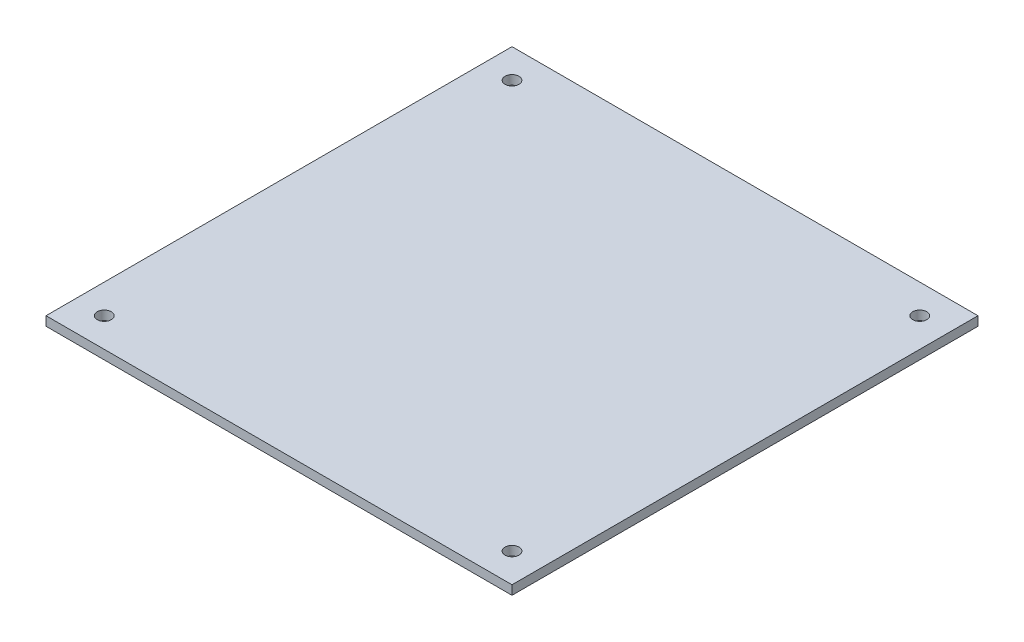
SolidWorks part; units mm, degrees
material "Beryllium S-65C, Vacuum Hot Pressed"
ref_plane "Front Plane" through (0, 0, 0) normal (0, 0, 1) x (1, 0, 0)
ref_plane "Top Plane" through (0, 0, 0) normal (0, 1, 0) x (1, 0, 0)
ref_plane "Right Plane" through (0, 0, 0) normal (1, 0, 0) x (0, 0, -1)
sketch "Sketch1" plane through (0, 0, 0) normal (0, 1, 0) x (1, 0, 0)
  line L1 (50.8, -50.8) -> (-50.8, -50.8)
  line L2 (50.8, -50.8) -> (50.8, 50.8)
  line L3 (50.8, 50.8) -> (-50.8, 50.8)
  line L4 (-50.8, -50.8) -> (-50.8, 50.8)
  line L5 (50.8, -50.8) -> (-50.8, 50.8) construction
  line L6 (50.8, 50.8) -> (-50.8, -50.8) construction
  point P0 (0, 0)
  dimension "D1" = 101.6
  dimension "D2" = 101.6
extrude "Boss-Extrude1" add sketch "Sketch1" along normal blind 2 contours L4 L3 L2 L1
sketch "Sketch3" plane through (0, 2, 0) normal (0, 1, 0) x (1, 0, 0)
  line L0 (-50.8, -50.8) -> (-50.8, 50.8) construction
  line L1 (50.8, -50.8) -> (-50.8, -50.8) construction
  line L2 (50.8, -50.8) -> (50.8, 50.8) construction
  line L3 (50.8, 50.8) -> (-50.8, 50.8) construction
  circle A0 centre (-44.45, -44.45) radius 1.524
  circle A1 centre (44.45, -44.45) radius 1.524
  circle A2 centre (44.45, 44.45) radius 1.524
  circle A3 centre (-44.45, 44.45) radius 1.524
  dimension "D1" = 3.048
  dimension "D2" = 2
  dimension "D3" = 6.35
  dimension "D4" = 6.35
  dimension "D6" = 6.35
  dimension "D7" = 6.35
  dimension "D5" = 2
extrude "Cut-Extrude1" cut sketch "Sketch3" against normal through all
